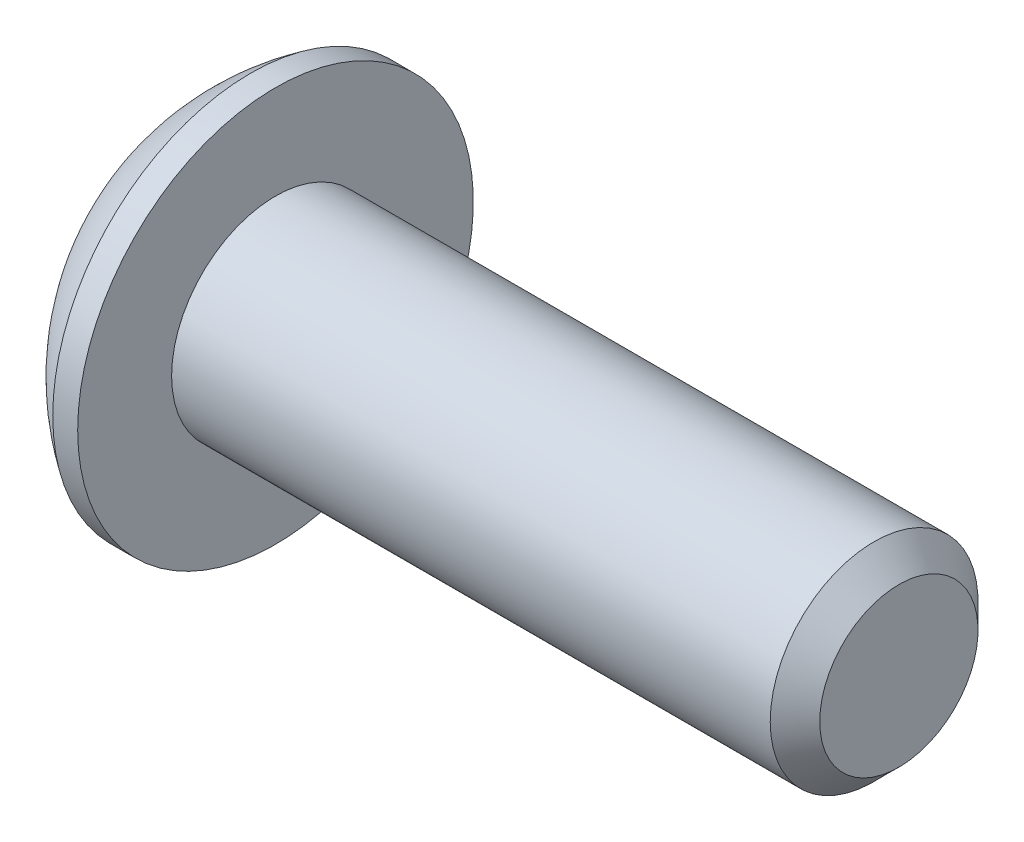
SolidWorks part; units mm, degrees
ref_plane "Plane1" through (0, 0, 0) normal (0, 0, 1) x (1, 0, 0)
ref_plane "Plane2" through (0, 0, 0) normal (0, 1, 0) x (1, 0, 0)
ref_plane "Plane3" through (0, 0, 0) normal (1, 0, 0) x (0, 0, -1)
sketch "BodySke" plane through (0, 0, 0) normal (0, 0, 1) x (1, 0, 0)
  line L0 (11.2014, 0) -> (11.2014, 1.209)
  line L1 (10.8229, 1.5875) -> (1.6764, 1.5875)
  line L2 (1.6764, 1.5875) -> (1.6764, 3.0226)
  line L3 (1.6764, 3.0226) -> (1.2954, 3.0226)
  line L4 (0, 0) -> (101.6, 0) construction
  line L5 (1.6764, -3.0226) -> (1.2954, -3.0226) construction
  line L6 (55.6768, -1.5875) -> (1.6764, -1.5875) construction
  line L7 (11.2014, 0) -> (0, 0)
  line L8 (0, 1.5113) -> (0, -1.5113) construction
  line L9 (0, 0) -> (0, 1.5113)
  line L10 (11.2014, 1.209) -> (10.8229, 1.5875)
  line L11 (11.2014, -1.209) -> (10.8229, -1.5875) construction
  line L12 (2.3114, 9.525) -> (2.3114, -1.5875) construction
  line L13 (1.6764, 9.525) -> (1.6764, -1.5875) construction
  arc A1 (0, 1.5113) -> (1.2954, 3.0226) centre (3.2925, 0) cw
  dimension "Diameter" = 3.175
  dimension "Length" = 9.525
  dimension "Head_dia" = 6.0452
  dimension "D1" = 3.0226
  dimension "Head_ht" = 1.6764
  dimension "Head_side_ht" = 0.381
  dimension "Minor_dia" = 2.4181
  dimension "Body_ch_ang" = 45
  dimension "Advance" = 0.635
  dimension "Thread_nom" = 9.525
revolve "BaseBody" add sketch "BodySke" angle 360 about L4
cosmetic thread "ThreadCosmetic" [suppressed] parameters "Thread_length"=8.89, "Thread_minor"=2.4181
sketch "Sketch2" plane through (0, 0, 0) normal (0, 0, 1) x (1, 0, 0)
  line L0 (0, 0.9906) -> (1.1176, 0.9906)
  line L1 (1.1176, 0.9906) -> (1.6895, 0)
  line L3 (1.6895, 0) -> (0, 0)
  line L4 (0, 0) -> (0, 0.9906)
  line L5 (0, -0.9906) -> (1.1176, -0.9906) construction
  line L6 (0, 0) -> (47.625, 0) construction
  dimension "D2" = 60
  dimension "PreBroach_depth" = 1.1176
  dimension "PreBroach_dia" = 1.9812
revolve "PreBroach" cut sketch "Sketch2" angle 360 about L6
sketch "Sketch3" plane through (0, 0, 0) normal (1, 0, 0) x (0, 0, -1)
  line L0 (-0.9906, -0.5719) -> (-0.9906, 0.5719)
  line L1 (-0.9906, 0.5719) -> (0, 1.1438)
  line L2 (0, 1.1438) -> (0.9906, 0.5719)
  line L3 (0.9906, 0.5719) -> (0.9906, -0.5719)
  line L4 (0.9906, -0.5719) -> (0, -1.1438)
  line L5 (0, -1.1438) -> (-0.9906, -0.5719)
  dimension "Hex_size" = 1.9812
  dimension "D3" = 1.9812
  dimension "D1" = 0.9906
  dimension "D2" = 0.9906
extrude "Hex" cut sketch "Sketch3" along normal blind 1.1176
sketch "Sketch4" plane through (0, 9.525, 0) normal (1, 0, 0) x (0, 0, -1)
  line L0 (0, -9.525) -> (1.2446, -9.525)
  line L1 (0, -9.525) -> (6.1484, -5.9752) construction
  line L2 (0, -9.525) -> (0.6223, -8.4471)
  line L3 (1.0085, -9.2654) -> (1.19, -9.1606)
  line L4 (0.7291, -8.7814) -> (0.9106, -8.6766)
  arc A0 (1.0085, -9.2654) -> (0.7291, -8.7814) centre (0, -9.525) ccw
  arc A1 (1.2446, -9.525) -> (1.19, -9.1606) centre (0, -9.525) ccw
  arc A2 (0.6223, -8.4471) -> (0.9106, -8.6766) centre (0, -9.525) cw
  dimension "Spline_n_dim" = 2.0828
  dimension "Spline_m_dim" = 2.4892
  dimension "D1" = 30
  dimension "D2" = 60
  dimension "Spline_p_dim" = 0.5588
  dimension "D3" = 0.2794
extrude "Spline" [suppressed] cut sketch "Sketch4" along normal blind 1.1176
pattern_circular "CirPattern1" [suppressed] count 6 every 60 about axis through (0, 0, 0) along (1, 0, 0)
sketch "ThdSchSke" plane through (0, 0, 0) normal (0, 0, 1) x (1, 0, 0)
  line L0 (2.3114, -1.209) -> (2.0464, -1.5875)
  line L1 (2.3114, -1.209) -> (2.5764, -1.5875)
  line L2 (2.5764, -1.5875) -> (2.5764, -1.9844)
  line L3 (-3.175, 0) -> (5.1513, 0) construction
  line L5 (2.5764, -1.9844) -> (2.0464, -1.9844)
  line L6 (2.0464, -1.9844) -> (2.0464, -1.5875)
  dimension "Diameter" = 3.175
  dimension "Thread_minor" = 2.4181
  dimension "SideAngle" = 55
  dimension "VeeAngle" = 70
  dimension "Overcut" = 3.9688
  dimension "Start" = 2.3114
revolve "ThreadSchematic" [suppressed] cut sketch "ThdSchSke" angle 360 about L3
pattern_linear "ThdSchPat" [suppressed]
equation "\"D1@BodySke\" = \"Head_dia@BodySke\" * .5"
equation "\"Thread_minor@ThreadCosmetic\" = \"Minor_dia@BodySke\""
equation "\"D1@Sketch3\" = \"Hex_size@Sketch3\" / 2"
equation "\"D2@Sketch3\" = \"D1@Sketch3\""
equation "\"D3@Sketch3\" = \"Hex_size@Sketch3\""
equation "\"D3@Sketch4\" = \"Spline_p_dim@Sketch4\" / 2"
equation "\"D1@Sketch4\" = \"D2@Sketch4\" / 2"
equation "\"Thread_length@ThreadCosmetic\" = ((sgn( (\"Length@BodySke\" - \"Advance@BodySke\" ) - \"Thread_nom@BodySke\" )-1)*( (\"Length@BodySke\" - \"Advance@BodySke\" ) - \"Thread_nom@BodySke\" ))/-2+ \"Thread_nom@BodySke\""
equation "\"Thread_minor@ThdSchSke\" = \"Minor_dia@BodySke\""
equation "\"Diameter@ThdSchSke\" = \"Diameter@BodySke\""
equation "\"Overcut@ThdSchSke\" = \"Diameter@BodySke\" * 1.25"
equation "\"Start@ThdSchSke\" = \"Head_ht@BodySke\" + \"Length@BodySke\" - \"Thread_length@ThreadCosmetic\"  '---Non-countersunk---"
equation "\"Num_threads@ThdSchPat\" = int( \"Thread_length@ThreadCosmetic\" / \"Advance@BodySke\" + 0.999 )  + 1"
equation "\"Advance@ThdSchPat\" = \"Thread_length@ThreadCosmetic\" /  (\"Num_threads@ThdSchPat\" - 1) 'relax it"
equation "\"Num_threads@ThdSchPat\" = \"Num_threads@ThdSchPat\" - sgn( \"Num_threads@ThdSchPat\" - 1) '---chamfered tips only---"
